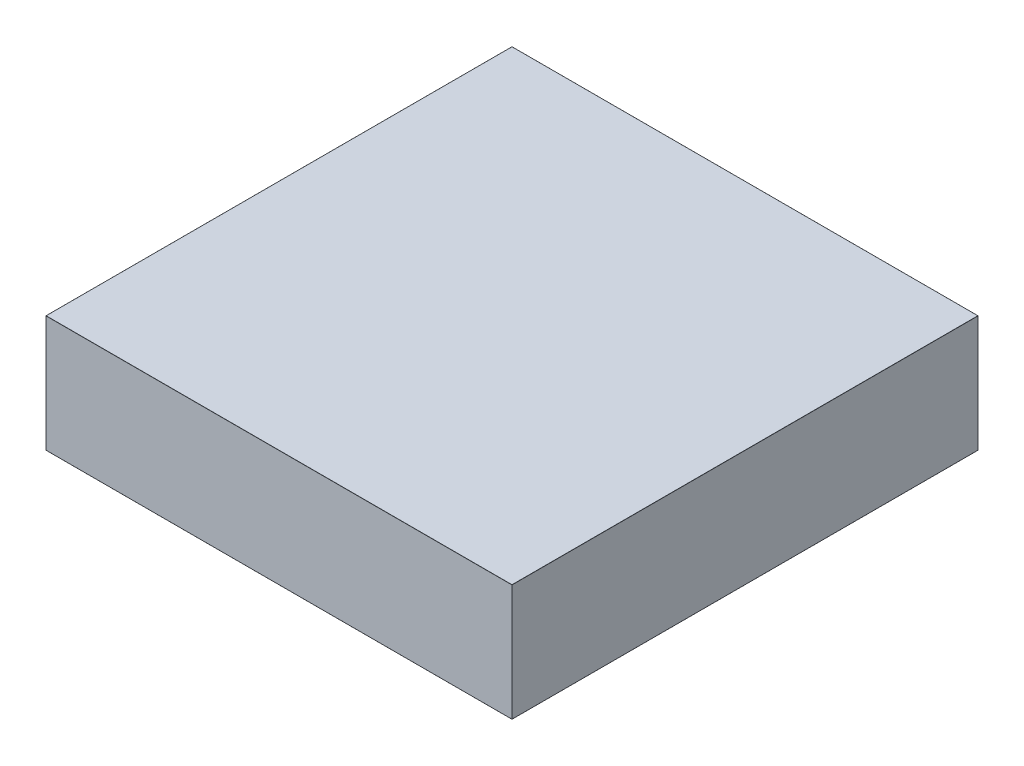
SolidWorks part; units mm, degrees
ref_plane "Front Plane" through (0, 0, 0) normal (0, 0, 1) x (1, 0, 0)
ref_plane "Top Plane" through (0, 0, 0) normal (0, 1, 0) x (1, 0, 0)
ref_plane "Right Plane" through (0, 0, 0) normal (1, 0, 0) x (0, 0, -1)
sketch "Sketch1" plane through (0, 0, 0) normal (0, 0, 1) x (1, 0, 0)
  line L1 (-200, -50) -> (200, -50)
  line L2 (-200, -50) -> (-200, 50)
  line L3 (-200, 50) -> (200, 50)
  line L4 (200, -50) -> (200, 50)
  line L5 (-200, -50) -> (200, 50) construction
  line L6 (-200, 50) -> (200, -50) construction
  point P0 (0, 0)
  dimension "D1" = 100
  dimension "D2" = 400
extrude "Boss-Extrude1" add sketch "Sketch1" along normal mid plane 400
fillet "Fillet1" radius 0.1 12 edges at (-200, 0, -200) (-200, -50, 0) (0, -50, -200) (200, -50, 0) (200, 0, -200) (0, -50, 200) (-200, 0, 200) (200, 0, 200) (200, 50, 0) (0, 50, 200) (-200, 50, 0) (0, 50, -200)
